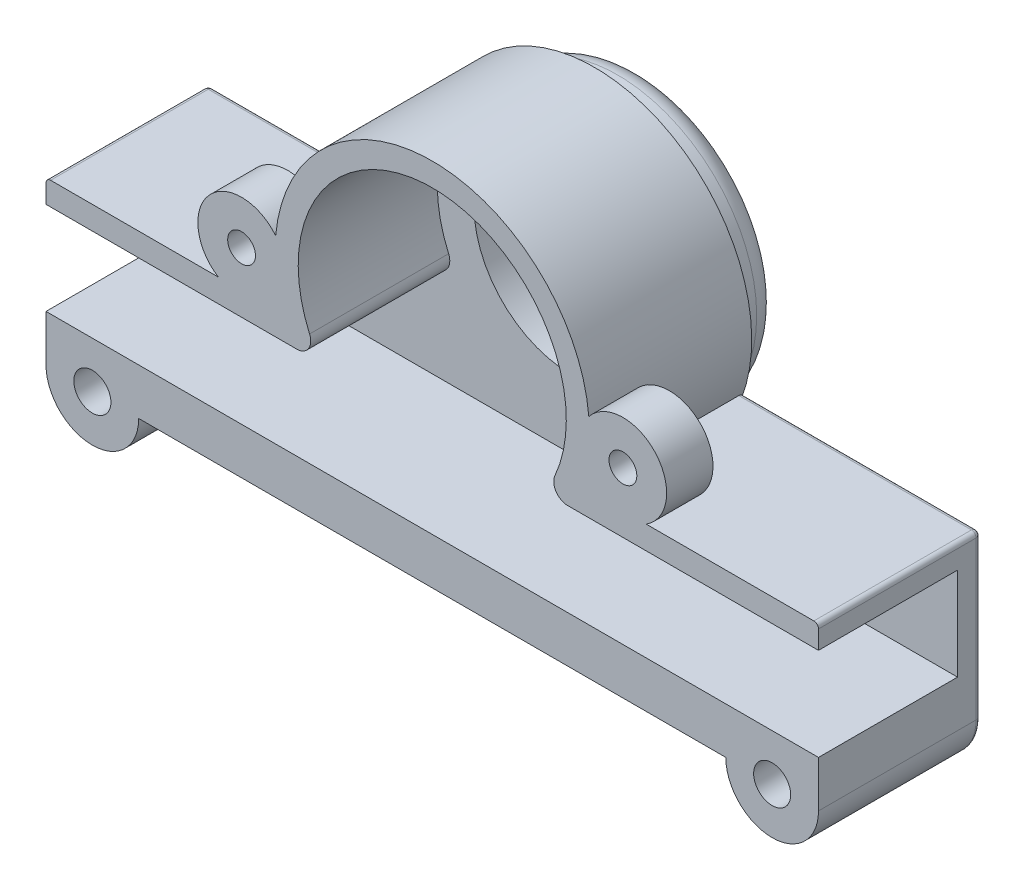
SolidWorks part; units mm, degrees
ref_plane "Front Plane" through (0, 0, 0) normal (0, 0, 1) x (1, 0, 0)
ref_plane "Top Plane" through (0, 0, 0) normal (0, 1, 0) x (1, 0, 0)
ref_plane "Right Plane" through (0, 0, 0) normal (1, 0, 0) x (0, 0, -1)
sketch "Sketch1" plane through (0, 0, 0) normal (0, 0, 1) x (1, 0, 0)
  line L1 (-83.3333, -35.8592) -> (-83.3333, -10.8592)
  line L2 (83.3333, -35.8592) -> (83.3333, -10.8592)
  line L3 (-83.3333, -10.8592) -> (-32.1356, -10.8592)
  line L4 (83.3333, -10.8592) -> (32.1356, -10.8592)
  line L5 (-83.3333, -35.8592) -> (-83.3333, -45.8592)
  line L6 (-63.3333, -45.8592) -> (0, -45.8592)
  line L7 (83.3333, -35.8592) -> (83.3333, -45.8592)
  line L8 (0, -45.8592) -> (63.3333, -45.8592)
  circle A0 centre (0, 0) radius 15
  arc A1 (32.1356, -10.8592) -> (-32.1356, -10.8592) centre (0, 0) ccw
  circle A6 centre (-73.3333, -45.8592) radius 4
  circle A7 centre (73.3333, -45.8592) radius 4
  arc A9 (-83.3333, -45.8592) -> (-63.3333, -45.8592) centre (-73.3333, -45.8592) ccw
  arc A10 (63.3333, -45.8592) -> (83.3333, -45.8592) centre (73.3333, -45.8592) ccw
  dimension "D1" = 30
  dimension "D2" = 67.8416
  dimension "D7" = 8
  dimension "D8" = 8
  dimension "D4" = 83.3333
  dimension "D5" = 83.3333
  dimension "D11" = 10
  dimension "D12" = 10
  dimension "D13" = 10
  dimension "D14" = 10
  dimension "D6" = 35.8592
  dimension "D10" = 35
  dimension "D15" = 10
extrude "Boss-Extrude2" add sketch "Sketch1" along normal blind 5
sketch "Sketch2" plane through (0, 0, 5) normal (0, 0, 1) x (1, 0, 0)
  line L0 (-83.3333, -35.8592) -> (83.3333, -35.8592)
  line L1 (-83.3333, -45.8592) -> (-83.3333, -10.8592) construction
  line L2 (83.3333, -10.8592) -> (83.3333, -45.8592) construction
  line L3 (-83.3333, -15.8592) -> (-24.1847, -15.8592)
  line L4 (24.1847, -15.8592) -> (83.3333, -15.8592)
  line L5 (-32.1356, -10.8592) -> (-83.3333, -10.8592)
  line L6 (-83.3333, -10.8592) -> (-83.3333, -15.8592)
  line L7 (32.1356, -10.8592) -> (83.3333, -10.8592)
  line L8 (83.3333, -10.8592) -> (83.3333, -15.8592)
  line L9 (83.3333, -35.8592) -> (83.3333, -45.8592)
  line L12 (-83.3333, -35.8592) -> (-83.3333, -45.8592)
  line L13 (-63.3333, -45.8592) -> (63.3333, -45.8592)
  arc A0 (-24.1847, -15.8592) -> (24.1847, -15.8592) centre (0, 0) cw
  arc A1 (32.1356, -10.8592) -> (-32.1356, -10.8592) centre (0, 0) ccw construction
  arc A2 (-83.3333, -45.8592) -> (-63.3333, -45.8592) centre (-73.3333, -45.8592) ccw
  arc A4 (63.3333, -45.8592) -> (83.3333, -45.8592) centre (73.3333, -45.8592) ccw
  circle A5 centre (-73.3333, -45.8592) radius 4
  circle A7 centre (73.3333, -45.8592) radius 4
  point P11 (0, -35.8592)
  dimension "D4" = 8
  dimension "D6" = 8
  dimension "D1" = 20
  dimension "D2" = 35.8592
  dimension "D3" = 5
extrude "Boss-Extrude3" add sketch "Sketch2" along normal blind 30
sketch "Sketch4" plane through (0, 0, 0) normal (0, 0, -1) x (-1, 0, 0)
  circle A0 centre (0, 0) radius 15
  circle A1 centre (0, 0) radius 30
  circle A2 centre (0, 0) radius 15 construction
  dimension "D1" = 60
extrude "Boss-Extrude4" add sketch "Sketch4" along normal blind 10
sketch "Sketch5" plane through (0, 0, 5) normal (0, 0, 1) x (1, 0, 0)
  circle A0 centre (0, 0) radius 15
  circle A1 centre (0, 0) radius 21
  circle A2 centre (0, 0) radius 15 construction
  dimension "D1" = 42
sketch "Sketch7" plane through (0, 0, 35) normal (0, 0, 1) x (1, 0, 0)
  line L0 (-32.1356, -10.8592) -> (-83.3333, -10.8592) construction
  line L3 (83.3333, -10.8592) -> (32.1356, -10.8592) construction
  line L4 (-46.1356, -10.8592) -> (-32.1356, -10.8592)
  line L5 (46.1356, -10.8592) -> (32.1356, -10.8592)
  circle A0 centre (-41.1356, -2.8592) radius 3
  circle A1 centre (41.1356, -2.8592) radius 3
  arc A2 (-33.7832, 3.052) -> (-46.1356, -10.8592) centre (-41.1356, -2.8592) ccw
  arc A3 (32.1356, -10.8592) -> (-32.1356, -10.8592) centre (0, 0) ccw construction
  arc A4 (33.7832, 3.052) -> (46.1356, -10.8592) centre (41.1356, -2.8592) cw
  arc A5 (32.1356, -10.8592) -> (33.7832, 3.052) centre (0, 0) ccw
  arc A6 (-32.1356, -10.8592) -> (-33.7832, 3.052) centre (0, 0) cw
  dimension "D3" = 6
  dimension "D4" = 6
  dimension "D1" = 8
  dimension "D2" = 9
  dimension "D5" = 9
  dimension "D6" = 8
  dimension "D7" = 5
  dimension "D8" = 5
extrude "Boss-Extrude6" add sketch "Sketch7" against normal blind 10
fillet "Fillet1" radius 5 1 edges at (-30, 0, -10)
extrude "Cut-Extrude2" cut sketch "Sketch5" against normal blind 10
sketch "Sketch8" plane through (0, 0, -5) normal (0, 0, 1) x (1, 0, 0)
  circle A0 centre (0, 0) radius 18
  circle A1 centre (0, 0) radius 21 construction
  dimension "D1" = 3
extrude "Cut-Extrude3" cut sketch "Sketch8" against normal blind 2
fillet "Fillet2" radius 1 9 edges at (-83.3333, -28.3592, 0) (-73.3333, -55.8592, 0) (0, -45.8592, 0) (73.3333, -55.8592, 0) (83.3333, -28.3592, 0) (57.7345, -10.8592, 0) (83.3333, -10.8592, 17.5) (-83.3333, -10.8592, 17.5) (-57.7345, -10.8592, 0)
fillet "Fillet3" radius 3 2 edges at (24.1847, -15.8592, 20) (-24.1847, -15.8592, 20)
equation "\"column angle\" = 45deg "
equation "\"short_bearing_outer_width\" = 10mm "
equation "\"wheel base\" = 1561mm "
equation "\"track\" = 1354mm "
equation "\"turning radius\" = 2000mm "
equation "\"turn to lock\" = 0.75mm "
equation "\"steering arm length\" = 100mm "
equation "\"primary shaft small diameter\" = 16mm "
equation "\"primary shaft large diameter\" = 24mm "
equation "\"secondary shaft small diameter\" = 16mm "
equation "\"secondary shaft large diameter\" = 25mm "
equation "\"steering column length\" = 555mm "
equation "\"keyway_height\" = 1.39mm "
equation "\"keyway_width\" = 2.78mm "
equation "\"keyway_length\" = 30mm "
equation "\"steering wheel bolt width\" = 6mm "
equation "\"steering wheel bolt length\" = 40mm "
equation "\"bushing length\" = 40mm "
equation "\"bushing thickness\" = 3mm "
equation "\"u_joint clearance\" = 30mm "
equation "\"u_joint thickness\" = 7.5mm "
equation "\"horizontal shaft length\" = 90mm "
equation "\"column bushing diameter\" = \"primary shaft small diameter\" + 4 "
equation "\"column bushing distance\" = \"steering column length\"/4 "
equation "\"pinion width\" = 26.5mm "
equation "\"pin hole diameter\" = 10mm "
equation "\"rack hole to hole\" = 500mm "
equation "\"rack length\" = \"rack hole to hole\" + \"pin hole diameter\"*2 "
equation "\"max turning angle\" = atn(\"wheel base\" / (\"turning radius\" - 0.5 * \"track\")) "
equation "\"max travel\" = 2 * \"steering arm length\" * sin(0.5 * \"max turning angle\") "
equation "\"pitch diameter\" = \"max travel\"/(pi * \"turn to lock\") "
equation "\"number of teeth\" = 18mm "
equation "\"pressure angle\" = 20deg "
equation "\"module\" = \"pitch diameter\" / \"number of teeth\" "
equation "\"tie rod length\" = 305mm "
equation "\"tie rod inner diameter\" = 6.6mm "
equation "\"tie rod outer diameter\" = 8.1mm "
equation "\"D1@Sketch1\"=\"secondary shaft large diameter\"+5"
equation "\"D2@Sketch1\"=\"secondary shaft large diameter\"*2+\"pitch diameter\"/2"
equation "\"D4@Sketch1\"=\"rack hole to hole\"/6"
equation "\"D5@Sketch1\"=\"rack hole to hole\"/6"
equation "\"D6@Sketch1\"=\"pitch diameter\"/2+20-\"module\""
equation "\"D2@Sketch2\"=\"pitch diameter\"/2 + 20-\"module\""
